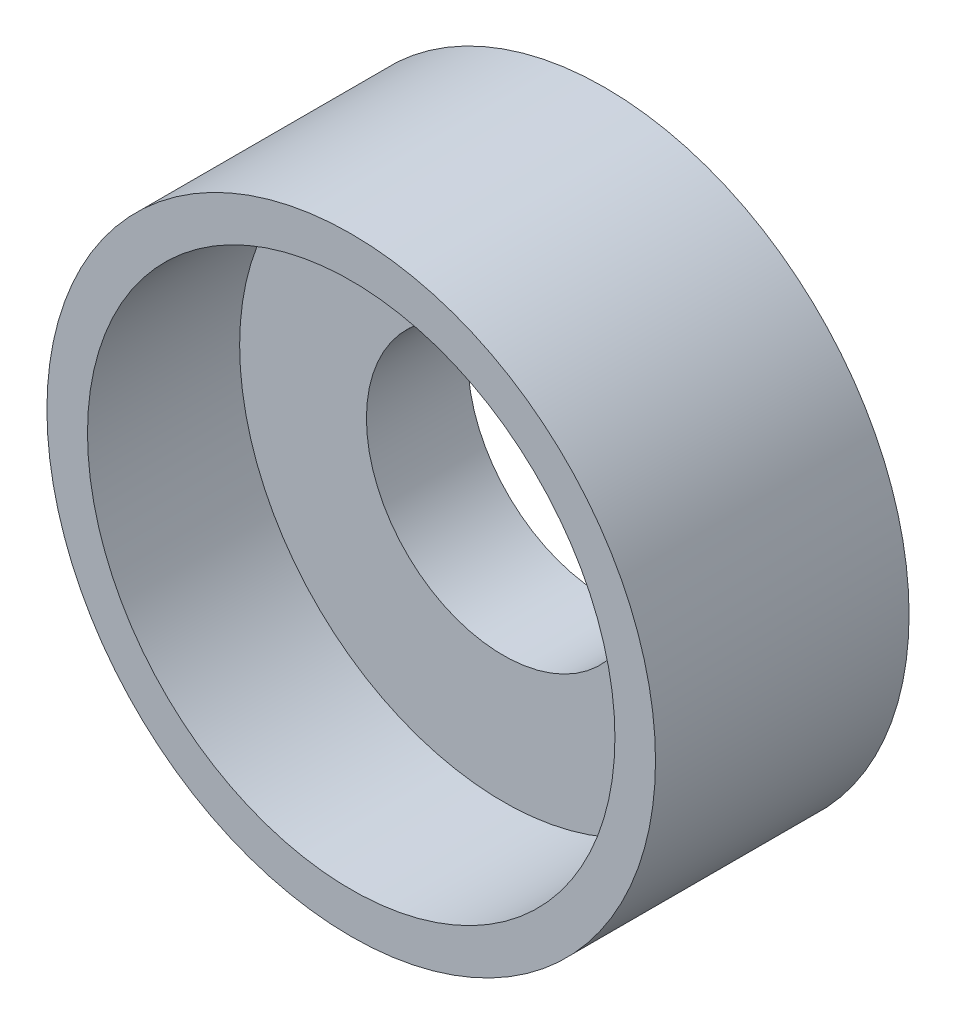
SolidWorks part; units mm, degrees
ref_plane "Front Plane" through (0, 0, 0) normal (0, 0, 1) x (1, 0, 0)
ref_plane "Top Plane" through (0, 0, 0) normal (0, 1, 0) x (1, 0, 0)
ref_plane "Right Plane" through (0, 0, 0) normal (1, 0, 0) x (0, 0, -1)
sketch "Sketch1" plane through (0, 0, 0) normal (0, 0, 1) x (1, 0, 0)
  circle A0 centre (0, 0) radius 30
  circle A1 centre (0, 0) radius 26
  dimension "D1" = 60
  dimension "D2" = 52
extrude "Boss-Extrude1" add sketch "Sketch1" along normal blind 25
sketch "Sketch2" plane through (0, 0, 0) normal (0, 0, -1) x (-1, 0, 0)
  circle A0 centre (0, 0) radius 26
  circle A1 centre (0, 0) radius 13.5
extrude "Boss-Extrude2" add sketch "Sketch2" against normal blind 10
